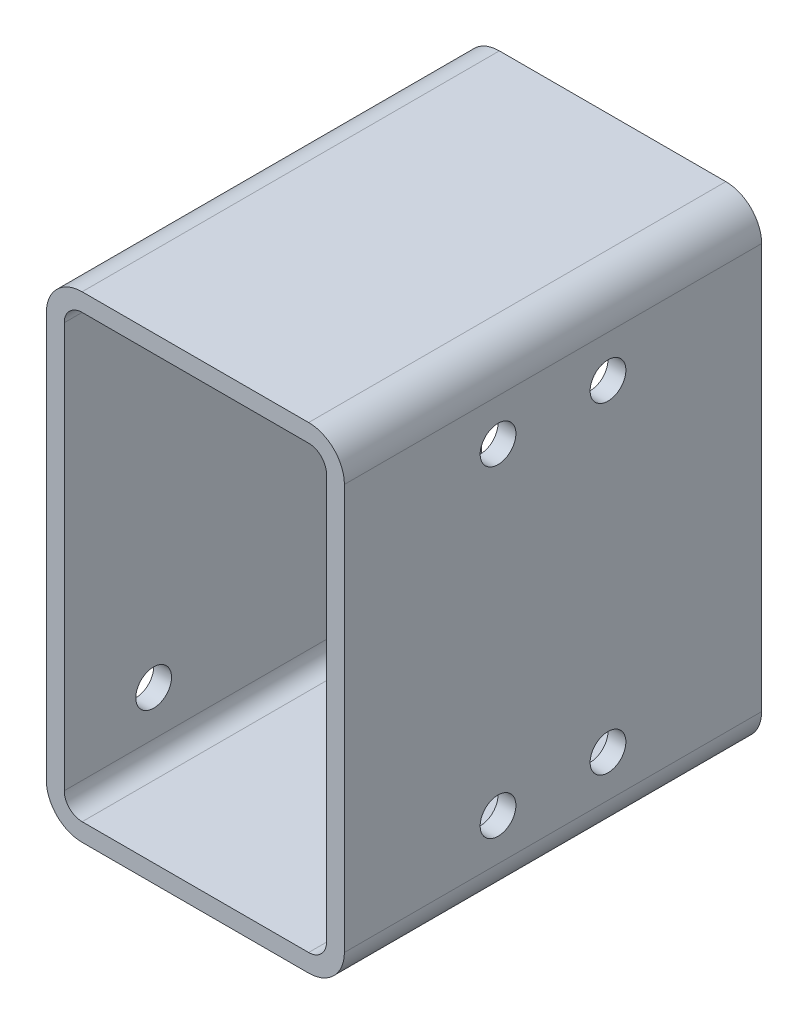
SolidWorks part; units mm, degrees
material "Plain Carbon Steel"
ref_plane "Front Plane" through (0, 0, 0) normal (0, 0, 1) x (1, 0, 0)
ref_plane "Top Plane" through (0, 0, 0) normal (0, 1, 0) x (1, 0, 0)
ref_plane "Right Plane" through (0, 0, 0) normal (1, 0, 0) x (0, 0, -1)
sketch "Sketch1" plane through (0, 0, 0) normal (0, 0, 1) x (1, 0, 0)
  line L0 (19, 40) -> (-19, 40)
  line L1 (19, -37) -> (-19, -37)
  line L2 (22, -34) -> (22, 34)
  line L3 (19, 37) -> (-19, 37)
  line L4 (-22, -34) -> (-22, 34)
  line L5 (22, -37) -> (-22, 37) construction
  line L6 (22, 37) -> (-22, -37) construction
  line L7 (-25, -34) -> (-25, 34)
  line L8 (19, -40) -> (-19, -40)
  line L9 (25, -34) -> (25, 34)
  line L10 (22, -37) -> (-22, -37) construction
  line L11 (22, -37) -> (22, 37) construction
  line L12 (-22, -37) -> (-22, 37) construction
  line L13 (22, 37) -> (-22, 37) construction
  line L14 (-25, -40) -> (-25, 40) construction
  line L15 (25, -40) -> (-25, -40) construction
  line L16 (25, -40) -> (25, 40) construction
  line L17 (25, 40) -> (-25, 40) construction
  arc A0 (19, -37) -> (22, -34) centre (19, -34) ccw
  arc A1 (-19, -37) -> (-22, -34) centre (-19, -34) cw
  arc A2 (-19, 37) -> (-22, 34) centre (-19, 34) ccw
  arc A3 (22, 34) -> (19, 37) centre (19, 34) ccw
  arc A4 (-25, -34) -> (-19, -40) centre (-19, -34) ccw
  arc A5 (19, -40) -> (25, -34) centre (19, -34) ccw
  arc A6 (19, 40) -> (25, 34) centre (19, 34) cw
  arc A7 (-19, 40) -> (-25, 34) centre (-19, 34) ccw
  point P0 (0, 0)
  dimension "D4" = 3
  dimension "D5" = 6
  dimension "D1" = 50
  dimension "D2" = 80
  dimension "D3" = 3
extrude "Boss-Extrude1" [suppressed] add sketch "Sketch1" along normal mid plane 100
sketch "Sketch2" [suppressed] plane through (-25, 0, 0) normal (-1, 0, 0) x (0, 0, 1)
  line L1 (20, -26.5) -> (-20, -26.5) construction
  line L2 (20, -26.5) -> (20, 26.5) construction
  line L3 (20, 26.5) -> (-20, 26.5) construction
  line L4 (-20, -26.5) -> (-20, 26.5) construction
  line L5 (20, -26.5) -> (-20, 26.5) construction
  line L6 (20, 26.5) -> (-20, -26.5) construction
  circle A0 centre (-20, 26.5) radius 3.3
  circle A1 centre (20, 26.5) radius 3.3
  circle A2 centre (20, -26.5) radius 3.3
  circle A3 centre (-20, -26.5) radius 3.3
  point P0 (0, 0)
  dimension "D3" = 6.6
  dimension "D1" = 40
  dimension "D2" = 53
extrude "Cut-Extrude1" [suppressed] cut sketch "Sketch2" against normal through all
sketch "Sketch3" [suppressed] plane through (0, -37, 0) normal (0, 1, 0) x (1, 0, 0)
  line L0 (0, 0) -> (3.6, 0) construction
  line L1 (25, -50) -> (25, 50) construction
  line L2 (14.85, 18) -> (-7.65, 18) construction
  line L3 (14.85, 18) -> (14.85, -18) construction
  line L4 (14.85, -18) -> (-7.65, -18) construction
  line L5 (-7.65, 18) -> (-7.65, -18) construction
  line L6 (14.85, 18) -> (-7.65, -18) construction
  line L7 (14.85, -18) -> (-7.65, 18) construction
  line L8 (-25, -50) -> (-25, 50) construction
  circle A0 centre (-7.65, 0) radius 2.5
  circle A1 centre (-7.65, 18) radius 2.5
  circle A2 centre (-7.65, -18) radius 2.5
  circle A3 centre (14.85, 18) radius 2.5
  circle A4 centre (14.85, -18) radius 2.5
  dimension "D1" = 5
  dimension "D2" = 36
  dimension "D4" = 10.15
  dimension "D3" = 17.35
extrude "Cut-Extrude2" [suppressed] cut sketch "Sketch3" against normal through all
sketch "Sketch4" [suppressed] plane through (0, 0, 0) normal (0, 0, 1) x (1, 0, 0)
  line L0 (25, -34) -> (25, 34) construction
  line L1 (19, -40) -> (-19, -40) construction
  line L2 (-25, -34) -> (-25, 34) construction
  line L3 (19, 40) -> (-19, 40) construction
  line L4 (22, -34) -> (22, 34) construction
  line L5 (19, -37) -> (-19, -37) construction
  line L6 (-22, -34) -> (-22, 34) construction
  line L7 (19, 37) -> (-19, 37) construction
  line L8 (25, -34) -> (25, 34)
  line L9 (19, -40) -> (-19, -40)
  line L10 (-25, -34) -> (-25, 34)
  line L11 (19, 40) -> (-19, 40)
  line L12 (22, -34) -> (22, 34)
  line L13 (19, -37) -> (-19, -37)
  line L14 (-22, -34) -> (-22, 34)
  line L15 (19, 37) -> (-19, 37)
  arc A0 (25, 34) -> (19, 40) centre (19, 34) ccw construction
  arc A1 (19, -40) -> (25, -34) centre (19, -34) ccw construction
  arc A2 (-25, -34) -> (-19, -40) centre (-19, -34) ccw construction
  arc A3 (-19, 40) -> (-25, 34) centre (-19, 34) ccw construction
  arc A4 (22, 34) -> (19, 37) centre (19, 34) ccw construction
  arc A5 (19, -37) -> (22, -34) centre (19, -34) ccw construction
  arc A6 (-22, -34) -> (-19, -37) centre (-19, -34) ccw construction
  arc A7 (-19, 37) -> (-22, 34) centre (-19, 34) ccw construction
  arc A8 (25, 34) -> (19, 40) centre (19, 34) ccw
  arc A9 (19, -40) -> (25, -34) centre (19, -34) ccw
  arc A10 (-25, -34) -> (-19, -40) centre (-19, -34) ccw
  arc A11 (-19, 40) -> (-25, 34) centre (-19, 34) ccw
  arc A12 (22, 34) -> (19, 37) centre (19, 34) ccw
  arc A13 (19, -37) -> (22, -34) centre (19, -34) ccw
  arc A14 (-22, -34) -> (-19, -37) centre (-19, -34) ccw
  arc A15 (-19, 37) -> (-22, 34) centre (-19, 34) ccw
extrude "Boss-Extrude2" [suppressed] add sketch "Sketch4" along normal mid plane 1000
sketch "Sketch5" [suppressed] plane through (0, -40, 0) normal (0, -1, 0) x (1, 0, 0)
  line L0 (0, 275.729) -> (0, 77.6099) construction
  line L1 (7, -22) -> (-7, -22) construction
  line L2 (7, -22) -> (7, 22) construction
  line L3 (7, 22) -> (-7, 22) construction
  line L4 (-7, -22) -> (-7, 22) construction
  line L5 (7, -22) -> (-7, 22) construction
  line L6 (7, 22) -> (-7, -22) construction
  line L7 (-19, 450) -> (19, 450) construction
  line L8 (7, 388) -> (-7, 388) construction
  line L9 (7, 388) -> (7, 432) construction
  line L10 (7, 432) -> (-7, 432) construction
  line L11 (-7, 388) -> (-7, 432) construction
  line L12 (7, 388) -> (-7, 432) construction
  line L13 (7, 432) -> (-7, 388) construction
  line L14 (-122.9838, 0) -> (91.0788, 0) construction
  circle A0 centre (-7, 22) radius 3
  circle A1 centre (7, 22) radius 3
  circle A2 centre (-7, -22) radius 3
  circle A3 centre (7, -22) radius 3
  circle A4 centre (-7, 432) radius 3
  circle A5 centre (7, 432) radius 3
  circle A6 centre (-7, 388) radius 3
  circle A7 centre (7, 388) radius 3
  circle A8 centre (0, 410) radius 3
  circle A9 centre (7, -432) radius 3
  circle A10 centre (-7, -432) radius 3
  circle A11 centre (-7, -388) radius 3
  circle A12 centre (7, -388) radius 3
  circle A13 centre (0, -410) radius 3
  point P0 (0, 0)
  point P11 (0, 410)
  dimension "D1" = 6
  dimension "D2" = 14
  dimension "D3" = 44
  dimension "D4" = 18
extrude "Cut-Extrude3" [suppressed] cut sketch "Sketch5" against normal blind 20
sketch "Sketch6" [suppressed] plane through (0, 0, 0) normal (0, 0, 1) x (1, 0, 0)
  line L4 (22, -34) -> (22, 34)
  line L5 (-19, -37) -> (19, -37)
  line L6 (-22, 34) -> (-22, -34)
  line L7 (19, 37) -> (-19, 37)
  line L8 (22, -34) -> (22, 34)
  line L9 (-19, -37) -> (19, -37)
  line L10 (-22, 34) -> (-22, -34)
  line L11 (19, 37) -> (-19, 37)
  line L12 (19, 40) -> (-19, 40)
  line L13 (25, -34) -> (25, 34)
  line L14 (-19, -40) -> (19, -40)
  line L15 (-25, 34) -> (-25, -34)
  line L16 (19, 40) -> (-19, 40)
  line L17 (25, -34) -> (25, 34)
  line L18 (-19, -40) -> (19, -40)
  line L19 (-25, 34) -> (-25, -34)
  arc A4 (19, -37) -> (22, -34) centre (19, -34) ccw
  arc A5 (-22, -34) -> (-19, -37) centre (-19, -34) ccw
  arc A6 (-19, 37) -> (-22, 34) centre (-19, 34) ccw
  arc A7 (22, 34) -> (19, 37) centre (19, 34) ccw
  arc A8 (19, -37) -> (22, -34) centre (19, -34) ccw
  arc A9 (-22, -34) -> (-19, -37) centre (-19, -34) ccw
  arc A10 (-19, 37) -> (-22, 34) centre (-19, 34) ccw
  arc A11 (22, 34) -> (19, 37) centre (19, 34) ccw
  arc A12 (-19, 40) -> (-25, 34) centre (-19, 34) ccw
  arc A13 (25, 34) -> (19, 40) centre (19, 34) ccw
  arc A14 (19, -40) -> (25, -34) centre (19, -34) ccw
  arc A15 (-25, -34) -> (-19, -40) centre (-19, -34) ccw
  arc A16 (-19, 40) -> (-25, 34) centre (-19, 34) ccw
  arc A17 (25, 34) -> (19, 40) centre (19, 34) ccw
  arc A18 (19, -40) -> (25, -34) centre (19, -34) ccw
  arc A19 (-25, -34) -> (-19, -40) centre (-19, -34) ccw
  dimension "D1" = 0
  dimension "D2" = 0
extrude "Boss-Extrude3" [suppressed] add sketch "Sketch6" along normal mid plane 1200
sketch "Sketch7" [suppressed] plane through (-25, 0, 0) normal (-1, 0, 0) x (0, 0, 1)
  line L0 (0, 216.5319) -> (0, -154.0504) construction
  line L1 (-437.1299, 0) -> (-275.6774, 0) construction
  line L2 (-600, 34) -> (-600, -34) construction
  line L3 (-568, 22) -> (-582, 22) construction
  line L4 (-568, 22) -> (-568, -22) construction
  line L5 (-568, -22) -> (-582, -22) construction
  line L6 (-582, 22) -> (-582, -22) construction
  line L7 (-568, 22) -> (-582, -22) construction
  line L8 (-568, -22) -> (-582, 22) construction
  circle A0 centre (-582, 22) radius 3
  circle A1 centre (-568, 22) radius 3
  circle A2 centre (-568, -22) radius 3
  circle A3 centre (-582, -22) radius 3
  circle A4 centre (568, -22) radius 3
  circle A5 centre (582, -22) radius 3
  circle A6 centre (582, 22) radius 3
  circle A7 centre (568, 22) radius 3
  point P1 (-575, 0)
  dimension "D1" = 6
  dimension "D2" = 14
  dimension "D3" = 44
  dimension "D4" = 18
extrude "Cut-Extrude4" [suppressed] cut sketch "Sketch7" against normal through all and the other way through all
sketch "Sketch8" [suppressed] plane through (-25, 0, 0) normal (-1, 0, 0) x (0, 0, 1)
  line L0 (-582, 22) -> (-568, -22) construction
  line L1 (0, 84.5802) -> (0, -115.7286) construction
  circle A0 centre (-575, 0) radius 3
  circle A1 centre (-568, 22) radius 3 construction
  circle A2 centre (575, 0) radius 3
extrude "Cut-Extrude5" [suppressed] cut sketch "Sketch8" against normal blind 20
sketch "Sketch9" plane through (0, 0, 0) normal (0, 0, 1) x (1, 0, 0)
  line L4 (22, -34) -> (22, 34)
  line L5 (-19, -37) -> (19, -37)
  line L6 (-22, 34) -> (-22, -34)
  line L7 (19, 37) -> (-19, 37)
  line L8 (22, -34) -> (22, 34)
  line L9 (-19, -37) -> (19, -37)
  line L10 (-22, 34) -> (-22, -34)
  line L11 (19, 37) -> (-19, 37)
  line L12 (19, 40) -> (-19, 40)
  line L13 (25, -34) -> (25, 34)
  line L14 (-19, -40) -> (19, -40)
  line L15 (-25, 34) -> (-25, -34)
  line L16 (19, 40) -> (-19, 40)
  line L17 (25, -34) -> (25, 34)
  line L18 (-19, -40) -> (19, -40)
  line L19 (-25, 34) -> (-25, -34)
  arc A4 (19, -37) -> (22, -34) centre (19, -34) ccw
  arc A5 (-22, -34) -> (-19, -37) centre (-19, -34) ccw
  arc A6 (-19, 37) -> (-22, 34) centre (-19, 34) ccw
  arc A7 (22, 34) -> (19, 37) centre (19, 34) ccw
  arc A8 (19, -37) -> (22, -34) centre (19, -34) ccw
  arc A9 (-22, -34) -> (-19, -37) centre (-19, -34) ccw
  arc A10 (-19, 37) -> (-22, 34) centre (-19, 34) ccw
  arc A11 (22, 34) -> (19, 37) centre (19, 34) ccw
  arc A12 (-19, 40) -> (-25, 34) centre (-19, 34) ccw
  arc A13 (25, 34) -> (19, 40) centre (19, 34) ccw
  arc A14 (19, -40) -> (25, -34) centre (19, -34) ccw
  arc A15 (-25, -34) -> (-19, -40) centre (-19, -34) ccw
  arc A16 (-19, 40) -> (-25, 34) centre (-19, 34) ccw
  arc A17 (25, 34) -> (19, 40) centre (19, 34) ccw
  arc A18 (19, -40) -> (25, -34) centre (19, -34) ccw
  arc A19 (-25, -34) -> (-19, -40) centre (-19, -34) ccw
  dimension "D1" = 0
  dimension "D2" = 0
extrude "Boss-Extrude4" add sketch "Sketch9" along normal mid plane 70
sketch "Sketch10" plane through (0, -40, 0) normal (0, -1, 0) x (1, 0, 0)
  line L0 (-413.5216, 0) -> (284.1515, 0) construction
  line L1 (0, 0) -> (0, 35) construction
  line L2 (-19, 35) -> (19, 35) construction
  line L4 (9.225, -32) -> (-9.225, -32) construction
  line L5 (9.225, -32) -> (9.225, 22) construction
  line L6 (9.225, 22) -> (-9.225, 22) construction
  line L7 (-9.225, -32) -> (-9.225, 22) construction
  line L8 (9.225, -32) -> (-9.225, 22) construction
  line L9 (9.225, 22) -> (-9.225, -32) construction
  circle A0 centre (-9.225, 22) radius 3
  circle A1 centre (9.225, 22) radius 3
  circle A2 centre (9.225, -32) radius 3
  circle A3 centre (-9.225, -32) radius 3
  circle A4 centre (9.225, 32) radius 3
  circle A5 centre (-9.225, 32) radius 3
  circle A6 centre (9.225, -22) radius 3
  circle A7 centre (-9.225, -22) radius 3
  point P7 (0, -5)
  dimension "D1" = 6
  dimension "D2" = 18.45
  dimension "D3" = 54
  dimension "D4" = 13
extrude "Cut-Extrude6" [suppressed] cut sketch "Sketch10" against normal blind 20
sketch "Sketch11" plane through (-25, 0, 0) normal (-1, 0, 0) x (0, 0, 1)
  line L1 (20, -26.5) -> (-20, -26.5) construction
  line L2 (20, -26.5) -> (20, 26.5) construction
  line L3 (20, 26.5) -> (-20, 26.5) construction
  line L4 (-20, -26.5) -> (-20, 26.5) construction
  line L5 (20, -26.5) -> (-20, 26.5) construction
  line L6 (20, 26.5) -> (-20, -26.5) construction
  circle A0 centre (-20, 26.5) radius 3
  circle A1 centre (20, 26.5) radius 3
  circle A2 centre (20, -26.5) radius 3
  circle A3 centre (-20, -26.5) radius 3
  point P0 (0, 0)
  dimension "D1" = 6
  dimension "D2" = 53
  dimension "D3" = 40
extrude "Cut-Extrude7" cut sketch "Sketch11" against normal blind 20
sketch "Sketch12" plane through (25, 0, 0) normal (1, 0, 0) x (0, 0, -1)
  line L1 (9.225, -27) -> (-9.225, -27) construction
  line L2 (9.225, -27) -> (9.225, 27) construction
  line L3 (9.225, 27) -> (-9.225, 27) construction
  line L4 (-9.225, -27) -> (-9.225, 27) construction
  line L5 (9.225, -27) -> (-9.225, 27) construction
  line L6 (9.225, 27) -> (-9.225, -27) construction
  circle A0 centre (-9.225, 27) radius 3
  circle A1 centre (9.225, 27) radius 3
  circle A2 centre (9.225, -27) radius 3
  circle A3 centre (-9.225, -27) radius 3
  point P0 (0, 0)
  dimension "D1" = 6
  dimension "D2" = 18.45
  dimension "D3" = 54
extrude "Cut-Extrude8" cut sketch "Sketch12" against normal blind 20
equation "\"length\"= 100"
equation "\"D1@Boss-Extrude1\"=\"length\""
equation "\"D3@Sketch2\"=\"M6_clearence\""
equation "\"D1@Sketch3\"=\"M6_tap\""
equation "\"M5_tap\"=4.2mm"
equation "\"M5_clearence\"=5.5mm"
equation "\"M6_tap\"=5mm"
equation "\"M6_clearence\"=6.6mm"
equation "\"work_area_width\"=1100mm"
equation "\"work_area_depth\"=1000mm"
equation "\"D1@Boss-Extrude2\"=\"work_area_depth\""
equation "\"D1@Boss-Extrude3\"=\"work_area_width\" + (50*2)"
equation "\"D1@Boss-Extrude4\"=\"work_area_width\" + 130mm"
